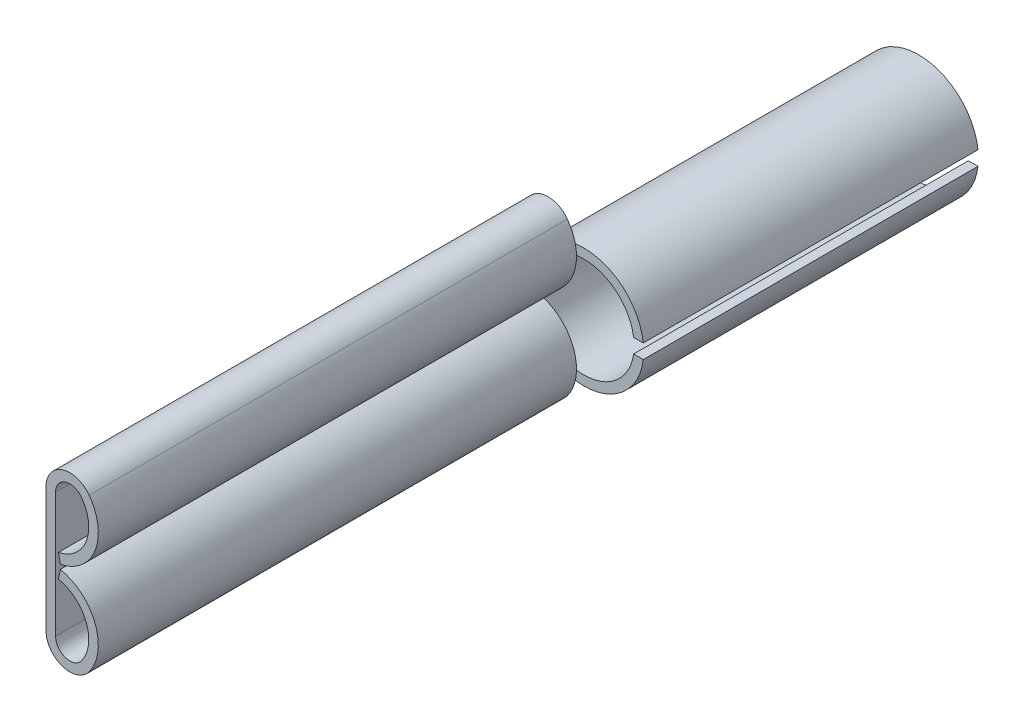
SolidWorks part; units mm, degrees
ref_plane "Спереди" through (0, 0, 0) normal (0, 0, 1) x (1, 0, 0)
ref_plane "Сверху" through (0, 0, 0) normal (0, 1, 0) x (1, 0, 0)
ref_plane "Справа" through (0, 0, 0) normal (1, 0, 0) x (0, 0, -1)
sketch "Эскиз1" plane through (0, 0, 0) normal (0, 0, 1) x (1, 0, 0)
  line L0 (-0.897, 2) -> (1.9366, 2) construction
  line L1 (0.2, 0.6956) -> (0.2, 3.3044)
  line L2 (0, 0.6956) -> (0, 3.3044)
  line L3 (0.2605, 2.2425) -> (0.3, 2.0464)
  line L4 (0.3, 1.9536) -> (0.2605, 1.7575)
  arc A0 (0.9041, 3.5988) -> (0.3, 2.0464) centre (0.1045, 3.0162) cw
  arc A1 (0.3, 1.9536) -> (0.9041, 0.4012) centre (0.1045, 0.9838) cw
  arc A2 (0, 3.3044) -> (0.9041, 3.5988) centre (0.5, 3.3044) cw
  arc A3 (0.9041, 0.4012) -> (0, 0.6956) centre (0.5, 0.6956) cw
  arc A4 (0.7425, 3.481) -> (0.2605, 2.2425) centre (0.1045, 3.0162) cw
  arc A5 (0.2, 3.3044) -> (0.7425, 3.481) centre (0.5, 3.3044) cw
  arc A6 (0.7425, 0.519) -> (0.2, 0.6956) centre (0.5, 0.6956) cw
  arc A7 (0.2605, 1.7575) -> (0.7425, 0.519) centre (0.1045, 0.9838) cw
  point P10 (0, 4)
  point P13 (0, 0)
  dimension "D4" = 0.5
  dimension "D1" = 4
  dimension "D2" = 0.3
  dimension "D3" = 0.3
  dimension "D5" = 0.2
extrude "Вытянуть1" add sketch "Эскиз1" along normal blind 10
sketch "Эскиз2" plane through (0, 0, 0) normal (0, 0, -1) x (-1, 0, 0)
  line L0 (0, 3.3044) -> (0, 0.6956) construction
  line L1 (-1.3331, 2) -> (0.5397, 2) construction
  line L3 (-2.491, 1.85) -> (-2.2892, 1.85)
  line L5 (-2.491, 2.15) -> (-2.2892, 2.15)
  arc A0 (-2.491, 1.85) -> (-2.491, 2.15) centre (-1.25, 2) ccw
  arc A1 (-0.2, 3.3044) -> (-0.7425, 3.481) centre (-0.5, 3.3044) ccw construction
  arc A2 (-0.7425, 0.519) -> (-0.2, 0.6956) centre (-0.5, 0.6956) ccw construction
  arc A3 (-2.2892, 1.85) -> (-2.2892, 2.15) centre (-1.25, 2) ccw
  dimension "D1" = 2.5
  dimension "D2" = 0.2
  dimension "D3" = 0.3
extrude "Вытянуть2" add sketch "Эскиз2" along normal blind 7
